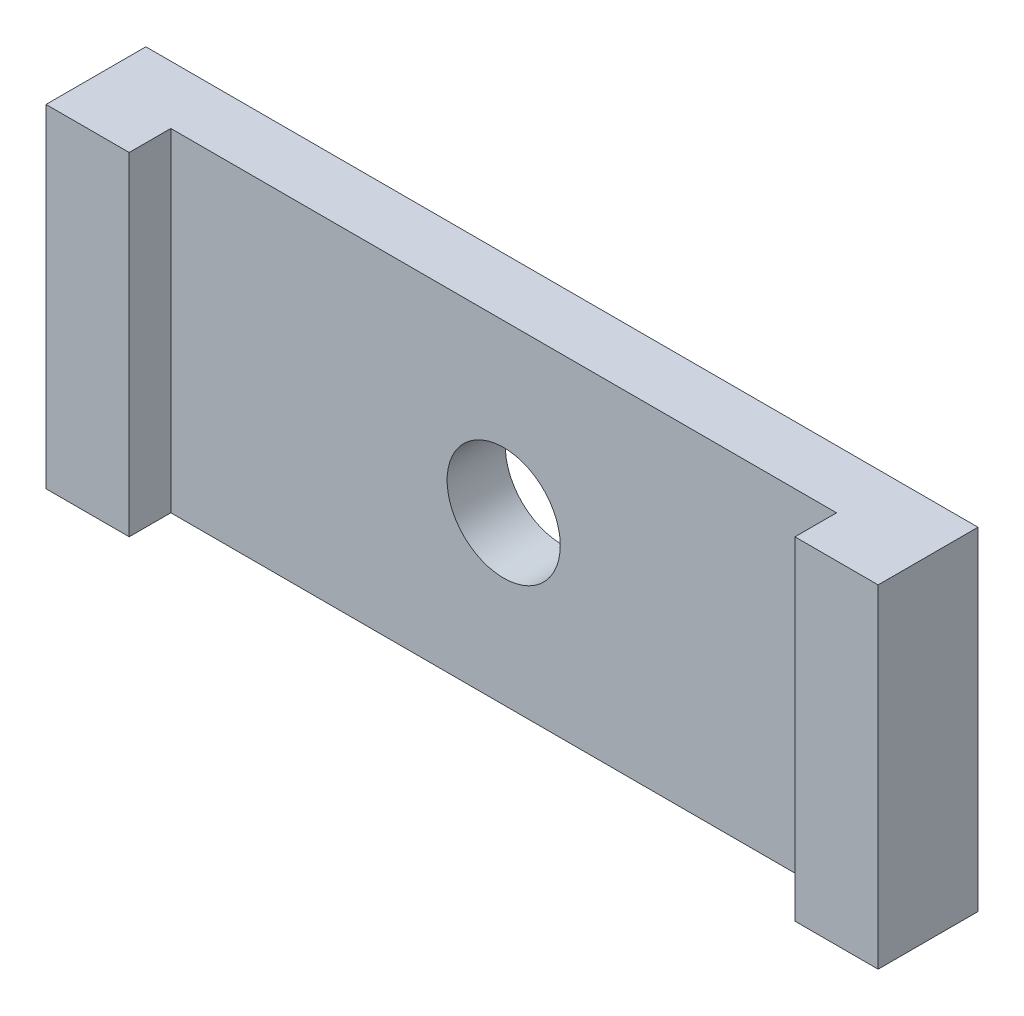
SolidWorks part; units mm, degrees
material "2014-T6"
ref_plane "Płaszczyzna przednia" through (0, 0, 0) normal (0, 0, 1) x (1, 0, 0)
ref_plane "Płaszczyzna górna" through (0, 0, 0) normal (0, 1, 0) x (1, 0, 0)
ref_plane "Płaszczyzna prawa" through (0, 0, 0) normal (1, 0, 0) x (0, 0, -1)
sketch "Szkic1" plane through (0, 0, 0) normal (0, 1, 0) x (1, 0, 0)
  line L0 (0, 0) -> (40, 0)
  line L1 (40, 0) -> (40, -2.5)
  line L2 (20, 0) -> (20, -5) construction
  line L3 (0, 0) -> (0, -2.5)
  line L4 (40, -2.5) -> (45, -2.5)
  line L5 (45, -2.5) -> (45, 3.5)
  line L6 (-5, -2.5) -> (-5, 3.5)
  line L7 (0, -2.5) -> (-5, -2.5)
  line L8 (-5, 3.5) -> (45, 3.5)
  line L9 (45, 3.5) -> (35.05, 3.5139)
  dimension "D1" = 2.5
  dimension "D2" = 40
  dimension "D4" = 5
  dimension "D5" = 3.5
  dimension "D6" = 3.5139
extrude "Dodanie-wyciągnięcie1" add sketch "Szkic1" along normal blind 20 contours L8 L6 L7 L3 L0 L1 L4 L5
sketch "Szkic2" plane through (0, 0, 0) normal (0, 0, 1) x (1, 0, 0)
  line L0 (20, 20) -> (20, 0) construction
  line L1 (0, 20) -> (40, 20) construction
  line L2 (0, 0) -> (40, 0) construction
  point P6 (20, 10)
hole_wizard "Otwór gwintowany M81" positions "Szkic 3D1" profile "Szkic3" tap size "M8" standard "ISO" end condition through all
sketch3d "Szkic 3D1"
  point P0 (20, 10, 0)
sketch "Szkic3" plane through (20, 10, 0) normal (1, 0, 0) x (0, -1, 0)
  line L0 (0, 0) -> (0, 3.5)
  line L1 (0, 3.5) -> (3.4, 3.5)
  line L2 (3.4, 3.5) -> (3.4, 0)
  line L5 (3.4, 0) -> (0, 0)
  line L11 (0, -6.35) -> (0, 107.95) construction
  dimension "Średnica otworu gwintowanego na wylot" = 6.8
  dimension "Głębokość otworu gwintowanego na wylot" = 3.5
cosmetic thread "Gwint otworu1" parameters "D2"=8
